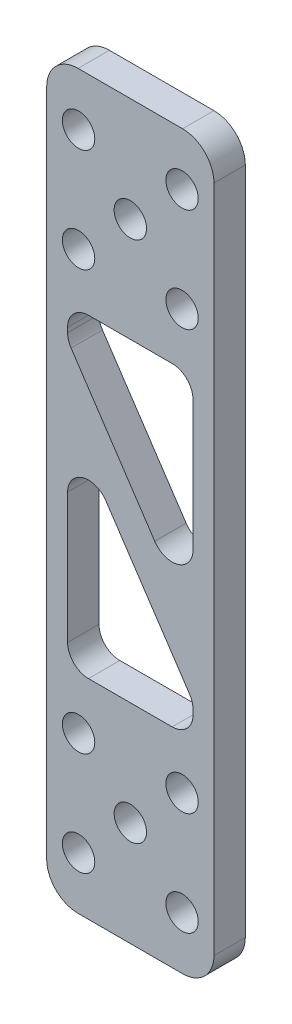
SolidWorks part; units mm, degrees
ref_plane "前视基准面" through (0, 0, 0) normal (0, 0, 1) x (1, 0, 0)
ref_plane "上视基准面" through (0, 0, 0) normal (0, 1, 0) x (1, 0, 0)
ref_plane "右视基准面" through (0, 0, 0) normal (1, 0, 0) x (0, 0, -1)
other "Configuration Table"
sketch "草图1" plane through (0, 0, 0) normal (0, 0, 1) x (1, 0, 0)
  line L0 (0, 60.2122) -> (0, -102.648) construction
  line L1 (-60.5647, 6.2167) -> (61.8958, 6.2167) construction
  line L2 (5, 16.2167) -> (-5, 16.2167)
  line L3 (-8, -66.7833) -> (-4, -108.7833)
  line L4 (0, -24.3301) -> (0, -46.8317) construction
  line L5 (8, -66.7833) -> (4, -108.7833)
  line L6 (-8, 13.2167) -> (-8, -66.7833)
  line L7 (-4, -108.7833) -> (4, -108.7833)
  line L8 (8, 13.2167) -> (8, -66.7833)
  line L12 (-27.2464, -43.7833) -> (27.2464, -43.7833) construction
  circle A0 centre (0, 6.2167) radius 7 construction
  circle A1 centre (-4.9497, 11.1665) radius 1.55
  circle A2 centre (4.9497, 11.1665) radius 1.55
  circle A3 centre (4.9497, 1.267) radius 1.55
  circle A4 centre (-4.9497, 1.267) radius 1.55
  circle A5 centre (0, -43.7833) radius 1.55
  circle A6 centre (0, -43.7833) radius 7 construction
  circle A7 centre (4.9497, -38.8335) radius 1.55
  circle A8 centre (-4.9497, -38.8335) radius 1.55
  arc A9 (8, 13.2167) -> (5, 16.2167) centre (5, 13.2167) ccw
  arc A10 (-8, 13.2167) -> (-5, 16.2167) centre (-5, 13.2167) cw
  circle A11 centre (4.9497, -48.733) radius 1.55
  circle A12 centre (-4.9497, -48.733) radius 1.55
  circle A13 centre (0, 6.2167) radius 1.55
  point P18 (0, 0)
  point P39 (0, -108.7833)
  point P44 (0, 6.2167)
  point P46 (0, -43.7833)
  dimension "D2" = 14
  dimension "D3" = 3.1
  dimension "D6" = 3.1
  dimension "D7" = 0
  dimension "D14" = 4
  dimension "D15" = 8
  dimension "D16" = 3.1
  dimension "D17" = 80
  dimension "D9" = 3
  dimension "D8" = 3.1
  dimension "D13" = 14
  dimension "D5" = 50
  dimension "D10" = 16
  dimension "D11" = 125
  dimension "D12" = 115
  dimension "D4" = 4
extrude "凸台-拉伸1" add sketch "草图1" along normal blind 3
sketch "草图2" plane through (0, 0, 0) normal (0, 0, -1) x (-1, 0, 0)
  line L0 (-14.1091, -98.7833) -> (16.5699, -98.7833)
  line L1 (16.5699, -98.7833) -> (16.5699, -119.0749)
  line L2 (16.5699, -119.0749) -> (-14.1091, -119.0749)
  line L3 (-14.1091, -119.0749) -> (-14.1091, -98.7833)
  line L4 (4, -108.7833) -> (-4, -108.7833) construction
  dimension "D1" = 10
extrude "切除-拉伸1" cut sketch "草图2" against normal blind 10
sketch "草图3" plane through (0, 0, 0) normal (0, 0, -1) x (-1, 0, 0)
  line L0 (4.9524, -98.7833) -> (-4.9524, -98.7833) construction
  circle A0 centre (0, -83.7833) radius 1
  circle A1 centre (0, -90.7833) radius 1
  circle A2 centre (0, -73.7833) radius 1
  dimension "D3" = 2
  dimension "D1" = 15
  dimension "D2" = 8
  dimension "D4" = 25
extrude "切除-拉伸2" cut sketch "草图3" against normal blind 20
sketch "草图4" plane through (0, 0, 0) normal (0, 0, -1) x (-1, 0, 0)
  line L0 (-8, -66.7833) -> (-8, 13.2167) construction
  line L1 (-8, -53.7833) -> (15.9609, -53.7833)
  line L2 (-8, -53.7833) -> (-8, -106.112)
  line L3 (-8, -106.112) -> (15.9609, -106.112)
  line L4 (15.9609, -53.7833) -> (15.9609, -106.112)
  circle A0 centre (0, -43.7833) radius 1.55 construction
  dimension "D1" = 10
extrude "切除-拉伸3" cut sketch "草图4" against normal blind 10
fillet "圆角1" radius 3 2 edges at (-8, -53.7833, 1.5) (8, -53.7833, 1.5)
sketch "草图5" plane through (0, 0, 0) normal (0, 0, -1) x (-1, 0, 0)
  line L0 (8, 13.2167) -> (8, -50.7833) construction
  line L1 (-6, -3.733) -> (6, -3.733)
  line L2 (-6, -3.733) -> (-6, -33.8335)
  line L3 (-6, -33.8335) -> (6, -33.8335)
  line L4 (6, -3.733) -> (6, -33.8335)
  line L5 (-8, -50.7833) -> (-8, 13.2167) construction
  line L6 (-6, -18.7833) -> (6, -18.7833) construction
  line L7 (-6, -30.7833) -> (6, -12.7833)
  line L8 (-6, -24.7833) -> (6, -6.7833)
  circle A0 centre (4.9497, 1.267) radius 1.55 construction
  circle A1 centre (4.9497, -38.8335) radius 1.55 construction
  dimension "D4" = 5
  dimension "D1" = 2
  dimension "D2" = 2
  dimension "D3" = 5
  dimension "D5" = 6
  dimension "D6" = 6
  dimension "D7" = 6
extrude "切除-拉伸4" cut sketch "草图5" against normal through all contours L6 L7 L2 L3 L4 | L2 L6 L8 L4 L1 | L6 L2 L8 | L7 L6 L4
fillet "圆角2" radius 2 8 edges at (6, -3.733, 1.5) (-6, -3.733, 1.5) (-6, -6.7833, 1.5) (6, -24.7833, 1.5) (6, -30.7833, 1.5) (-6, -12.7833, 1.5) (6, -33.8335, 1.5) (-6, -33.8335, 1.5)
